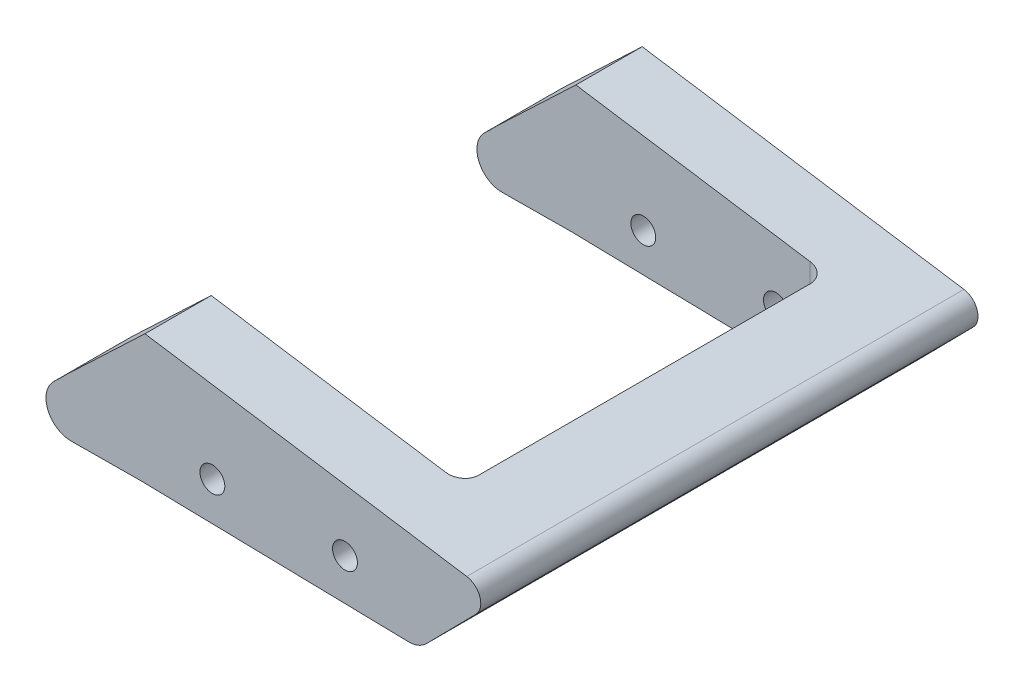
SolidWorks part; units mm, degrees
ref_plane "前视基准面" through (0, 0, 0) normal (0, 0, 1) x (1, 0, 0)
ref_plane "上视基准面" through (0, 0, 0) normal (0, 1, 0) x (1, 0, 0)
ref_plane "右视基准面" through (0, 0, 0) normal (1, 0, 0) x (0, 0, -1)
other "Configuration Table"
sketch "草图1" plane through (0, 0, 0) normal (0, 0, 1) x (1, 0, 0)
  line L1 (0, -55) -> (0, 55) construction
  line L3 (-12.7855, 4) -> (12.7855, 4)
  line L4 (-12.7855, 4) -> (-12.7855, -4)
  line L5 (-12.7855, -4) -> (12.7855, -4)
  line L6 (12.7855, 4) -> (12.7855, -4)
  line L7 (-12.7855, 4) -> (12.7855, -4) construction
  line L8 (-12.7855, -4) -> (12.7855, 4) construction
  circle A0 centre (-8, 0) radius 1.5
  circle A1 centre (8, 0) radius 1.5
  point P2 (0, 0)
  dimension "D1" = 3
  dimension "D2" = 8
  dimension "D3" = 8
extrude "凸台-拉伸1" add sketch "草图1" along normal blind 60
sketch "草图2" plane through (0, 0, 0) normal (0, 0, -1) x (-1, 0, 0)
  line L0 (-26.5585, 4.5838) -> (16.137, 11.1249)
  line L4 (-12.7855, 4) -> (-12.7855, -4)
  line L5 (-12.7855, -4) -> (12.7855, -4)
  line L6 (16.6771, -4.482) -> (25.055, -4.5427)
  line L7 (25.7547, 2.0028) -> (16.137, 11.1249)
  line L8 (16.137, 11.1249) -> (-27.4701, 55.3689)
  line L9 (-27.4701, 55.3689) -> (-52.3976, 30.8002)
  line L24 (-52.3976, 30.8002) -> (-17.8339, -4.2683)
  line L25 (-15.6342, -5.1617) -> (16.6771, -4.482)
  line L26 (16.6771, -4.482) -> (25.055, -4.5427)
  line L27 (25.7547, 2.0028) -> (16.137, 11.1249)
  line L28 (16.137, 11.1249) -> (-27.4701, 55.3689)
  line L29 (-27.4701, 55.3689) -> (-52.3976, 30.8002)
  line L30 (-52.3976, 30.8002) -> (-17.8339, -4.2683)
  line L31 (-15.6342, -5.1617) -> (16.6771, -4.482)
  line L32 (12.7855, -4) -> (12.7855, 4)
  line L33 (12.7855, 4) -> (-12.7855, 4)
  line L34 (-12.7855, 4) -> (-12.7855, -4)
  line L35 (-12.7855, -4) -> (12.7855, -4)
  line L36 (12.7855, -4) -> (12.7855, 4)
  line L37 (12.7855, 4) -> (-12.7855, 4)
  arc A3 (25.055, -4.5427) -> (27.1059, 0.6668) centre (25.0767, -1.5428) ccw
  arc A4 (25.7547, 2.0028) -> (27.1059, 0.6668) centre (44.5459, 19.6566) ccw
  arc A5 (-17.8339, -4.2683) -> (-15.6342, -5.1617) centre (-15.6973, -2.1624) ccw
  arc A9 (25.055, -4.5427) -> (27.1059, 0.6668) centre (25.0767, -1.5428) ccw
  arc A10 (25.7547, 2.0028) -> (27.1059, 0.6668) centre (44.5459, 19.6566) ccw
  arc A11 (-17.8339, -4.2683) -> (-15.6342, -5.1617) centre (-15.6973, -2.1624) ccw
  dimension "D1" = 0
  dimension "D2" = 0
extrude "凸台-拉伸2" add sketch "草图2" against normal up to surface (60 mm away) up to face at (-6.5, 0, 60)
sketch "草图3" plane through (-0.1016, -4.8307, 0) normal (-0.021, -0.9998, 0) x (0.9998, -0.021, 0)
  line L0 (15.7393, 0) -> (-16.5791, 0) construction
  line L1 (-14, 8) -> (14, 8)
  line L2 (-14, 8) -> (-14, 52)
  line L3 (-14, 52) -> (14, 52)
  line L4 (14, 8) -> (14, 52)
  line L5 (-14, 8) -> (14, 52) construction
  line L6 (-14, 52) -> (14, 8) construction
  line L9 (15.7393, 60) -> (-16.5791, 60) construction
  point P0 (0, 30)
  dimension "D1" = 8
  dimension "D2" = 28
  dimension "D3" = 8
extrude "切除-拉伸1" cut sketch "草图3" against normal through all
fillet "圆角3" radius 2 1 edges at (26.5585, 4.5838, 30)
sketch "草图5" plane through (0.0316, -4.3609, 0) normal (0.0072, -1, 0) x (1, 0.0072, 0)
  line L0 (13.8578, 52) -> (-14.131, 52) construction
  line L1 (-14.131, 52) -> (-14.131, 8) construction
  line L2 (13.8578, 52) -> (-14.131, 52)
  line L3 (-14.131, 52) -> (-14.131, 8)
  line L4 (-14.131, 52) -> (-14.131, 42)
  line L5 (-14.131, 52) -> (-45.0526, 52)
  line L6 (-14.131, 42) -> (-45.0526, 42)
  line L7 (-45.0526, 52) -> (-45.0526, 42)
  line L9 (-14.131, 52) -> (-14.131, 42)
  line L10 (-14.131, 52) -> (-9.8243, 52)
  line L11 (-14.131, 42) -> (-9.8243, 42)
  line L12 (-9.8243, 52) -> (-9.8243, 42)
  line M2 (-16.7091, 0) -> (-16.7091, 60)
  line M4 (-25.0872, 60) -> (-25.0872, 0)
  dimension "D1" = 10
extrude "切除-拉伸3" cut sketch "草图5" against normal through all and the other way through all contours L5 L7 L6 M4 | L6 L5 M2 M4 | L6 L3 L5 M2 | L12 L2 L3 L11
fillet "圆角4" radius 2 3 edges at (-13.9376, 3.1135, 8) (14.0174, 0.6807, 8) (14.0174, 0.6807, 52)
sketch "草图6" plane through (0.0316, -4.3609, 0) normal (0.0072, -1, 0) x (1, 0.0072, 0)
  line L0 (-12.1318, 8) -> (11.8586, 8) construction
  line L1 (-14.131, 42) -> (-14.131, 10) construction
  line L2 (-12.1318, 8) -> (11.8586, 8)
  line L3 (-14.131, 42) -> (-14.131, 10) construction
  line L4 (-6.3481, 8) -> (-6.3481, 44.6901)
  line L5 (-6.3481, 8) -> (-50.5419, 8)
  line L6 (-6.3481, 44.6901) -> (-50.5419, 44.6901)
  line L7 (-50.5419, 8) -> (-50.5419, 44.6901)
extrude "切除-拉伸4" cut sketch "草图6" against normal through all and the other way through all
